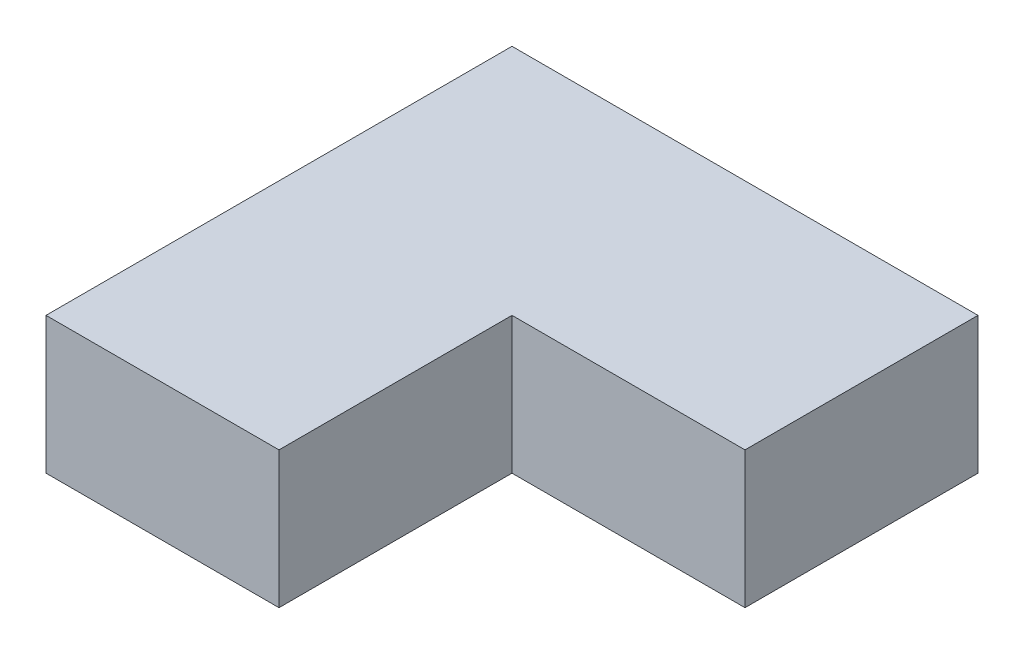
SolidWorks part; units mm, degrees
ref_plane "Front Plane" through (0, 0, 0) normal (0, 0, 1) x (1, 0, 0)
ref_plane "Top Plane" through (0, 0, 0) normal (0, 1, 0) x (1, 0, 0)
ref_plane "Right Plane" through (0, 0, 0) normal (1, 0, 0) x (0, 0, -1)
sketch "Sketch1" plane through (0, 0, 0) normal (0, 1, 0) x (1, 0, 0)
  line L1 (-37.5, 37.5) -> (37.5, 37.5)
  line L2 (-37.5, 37.5) -> (-37.5, -37.5)
  line L3 (-37.5, -37.5) -> (37.5, -37.5)
  line L4 (37.5, 37.5) -> (37.5, -37.5)
  line L5 (-37.5, 37.5) -> (37.5, -37.5) construction
  line L6 (-37.5, -37.5) -> (37.5, 37.5) construction
  point P0 (0, 0)
  dimension "D1" = 75
  dimension "D2" = 75
extrude "Boss-Extrude1" add sketch "Sketch1" along normal blind 22
sketch "Sketch2" plane through (0, 22, 0) normal (0, 1, 0) x (1, 0, 0)
  line L1 (37.5, -37.5) -> (0, -37.5)
  line L2 (37.5, -37.5) -> (37.5, 0)
  line L3 (37.5, 0) -> (0, 0)
  line L4 (0, -37.5) -> (0, 0)
extrude "Cut-Extrude1" cut sketch "Sketch2" against normal through all
